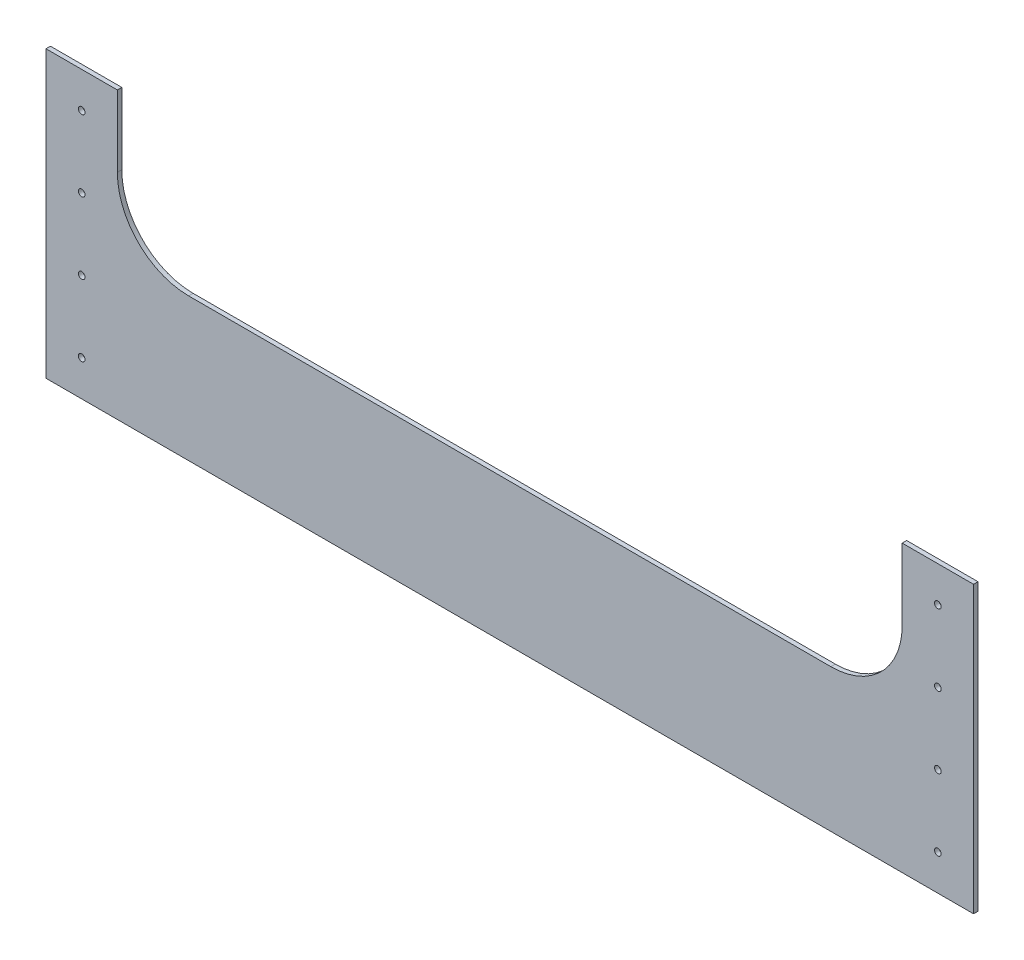
SolidWorks part; units mm, degrees
ref_plane "Front Plane" through (0, 0, 0) normal (0, 0, 1) x (1, 0, 0)
ref_plane "Top Plane" through (0, 0, 0) normal (0, 1, 0) x (1, 0, 0)
ref_plane "Right Plane" through (0, 0, 0) normal (1, 0, 0) x (0, 0, -1)
sketch "Sketch1" plane through (0, 0, 0) normal (0, 0, 1) x (1, 0, 0)
  line L0 (330.2, 0) -> (-330.2, 0)
  line L1 (-330.2, 0) -> (-330.2, 203.2)
  line L2 (-330.2, 203.2) -> (-279.4, 203.2)
  line L3 (-279.4, 203.2) -> (-279.4, 152.4)
  line L4 (-228.6, 101.6) -> (228.6, 101.6)
  line L5 (279.4, 152.4) -> (279.4, 203.2)
  line L6 (279.4, 203.2) -> (330.2, 203.2)
  line L7 (330.2, 203.2) -> (330.2, 0)
  line L8 (-330.2, 152.4) -> (-279.4, 203.2) construction
  line L9 (-304.8, 177.8) -> (-304.8, 127) construction
  line L10 (-304.8, 177.8) -> (304.8, 177.8) construction
  arc A0 (228.6, 101.6) -> (279.4, 152.4) centre (228.6, 152.4) ccw
  arc A1 (-279.4, 152.4) -> (-228.6, 101.6) centre (-228.6, 152.4) ccw
  circle A2 centre (-304.8, 177.8) radius 2.3813
  circle A3 centre (-304.8, 127) radius 2.3813
  circle A4 centre (-304.8, 76.2) radius 2.3813
  circle A5 centre (-304.8, 25.4) radius 2.3813
  circle A6 centre (304.8, 177.8) radius 2.3813
  circle A7 centre (304.8, 127) radius 2.3813
  circle A8 centre (304.8, 76.2) radius 2.3813
  circle A9 centre (304.8, 25.4) radius 2.3813
  point P3 (304.7978, 176.1486)
  point P4 (0, 0)
  point P11 (0, 101.6)
  point P23 (-304.8, 177.8)
  dimension "D5" = 50.8
  dimension "D6" = 4.7625
  dimension "D1" = 660.4
  dimension "D2" = 50.8
  dimension "D3" = 203.2
  dimension "D4" = 101.6
  dimension "D8" = 50.8
  dimension "D10" = 609.6
  dimension "D7" = 4
  dimension "D9" = 2
extrude "Boss-Extrude1" add sketch "Sketch1" along normal blind 3.175
